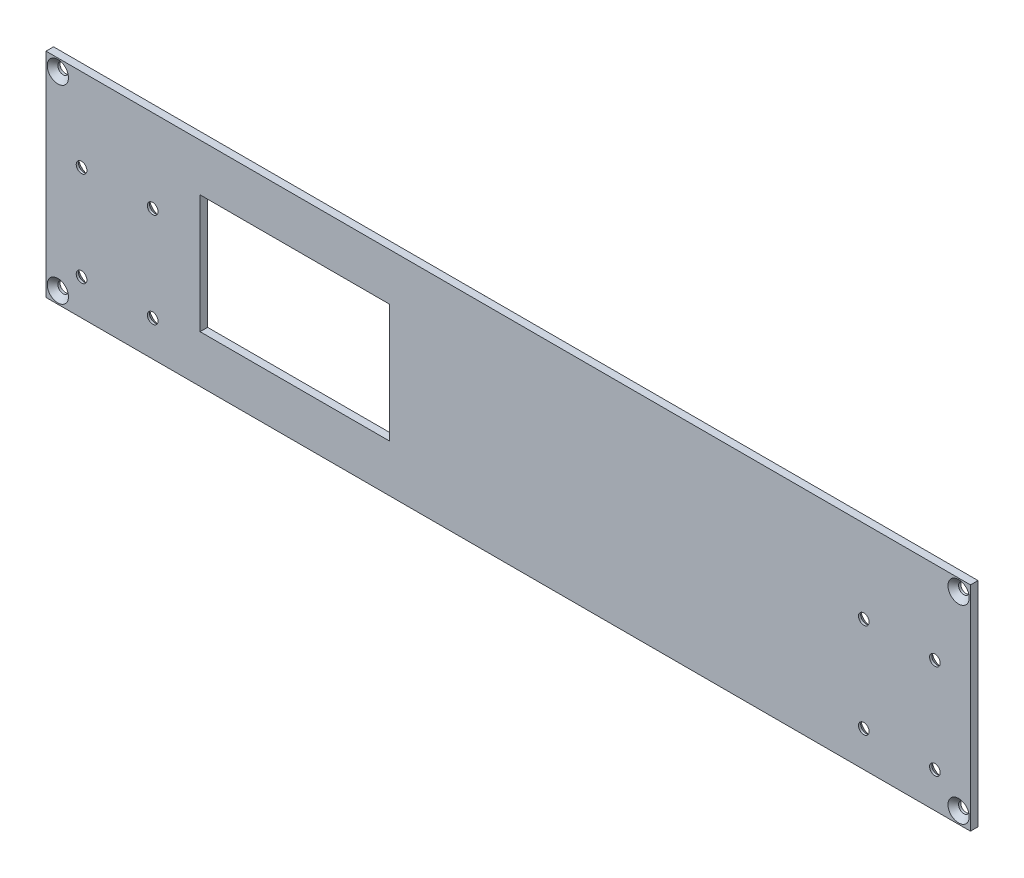
SolidWorks part; units mm, degrees
ref_plane "Front Plane" through (0, 0, 0) normal (0, 0, 1) x (1, 0, 0)
ref_plane "Top Plane" through (0, 0, 0) normal (0, 1, 0) x (1, 0, 0)
ref_plane "Right Plane" through (0, 0, 0) normal (1, 0, 0) x (0, 0, -1)
sketch "Sketch1" plane through (0, 0, 0) normal (0, 0, 1) x (1, 0, 0)
  line L1 (-195, -45) -> (195, -45)
  line L2 (-195, -45) -> (-195, 45)
  line L3 (-195, 45) -> (195, 45)
  line L4 (195, -45) -> (195, 45)
  line L5 (-195, -45) -> (195, 45) construction
  line L6 (-195, 45) -> (195, -45) construction
  point P0 (0, 0)
  dimension "D1" = 390
  dimension "D2" = 90
extrude "Boss-Extrude1" add sketch "Sketch1" along normal blind 3.175
hole_wizard "CSK for M4 SFHCS1" positions "Sketch3" profile "Sketch5" countersink size "M4" standard "ANSI Metric" end condition through all
sketch "Sketch3" plane through (0, 0, 0) normal (0, 0, -1) x (-1, 0, 0)
  line L1 (-180, -30) -> (-150, -30)
  line L2 (-180, -30) -> (-180, 10)
  line L3 (-180, 10) -> (-150, 10)
  line L4 (-150, -30) -> (-150, 10)
  line L5 (-180, -30) -> (-150, 10) construction
  line L6 (-180, 10) -> (-150, -30) construction
  line L7 (195, -45) -> (-195, -45) construction
  line L8 (-195, -45) -> (-195, 45) construction
  point P2 (-150, 10)
  point P69 (-180, -30)
  point P70 (-180, 10)
  point P71 (-150, -30)
  dimension "D1" = 30
  dimension "D2" = 40
  dimension "D3" = 15
  dimension "D4" = 15
sketch "Sketch5" plane through (150, 10, 0) normal (1, 0, 0) x (0, 1, 0)
  line L0 (0, 0) -> (0, 3.175)
  line L1 (0, 3.175) -> (2.25, 3.175)
  line L2 (2.25, 3.175) -> (2.25, 2.23)
  line L3 (2.25, 2.23) -> (4.48, 0)
  line L5 (4.48, 0) -> (0, 0)
  line L6 (-2.25, 2.23) -> (-4.48, 0) construction
  line L11 (0, -6.35) -> (0, 107.95) construction
  dimension "Thru Hole Dia." = 4.5
  dimension "Thru Hole Depth" = 3.175
  dimension "Near C'Sink Dia." = 8.96
  dimension "Near C'Sink Angle" = 90
hole_wizard "CSK for M4 SFHCS3" positions "Sketch6" profile "Sketch7" countersink size "M4" standard "ANSI Metric" end condition through all
sketch "Sketch6" plane through (0, 0, 3.175) normal (0, 0, 1) x (1, 0, 0)
  line L0 (190, 40) -> (190, -40)
  line L1 (195, -45) -> (195, 45) construction
  point P1 (190, 40)
  point P2 (190, -40)
  point P6 (190, 0)
  dimension "D1" = 80
  dimension "D2" = 5
sketch "Sketch7" plane through (190, 40, 3.175) normal (1, 0, 0) x (0, -1, 0)
  line L0 (0, 0) -> (0, 3.175)
  line L1 (0, 3.175) -> (2.25, 3.175)
  line L2 (2.25, 3.175) -> (2.25, 2.23)
  line L3 (2.25, 2.23) -> (4.48, 0)
  line L5 (4.48, 0) -> (0, 0)
  line L6 (-2.25, 2.23) -> (-4.48, 0) construction
  line L11 (0, -6.35) -> (0, 107.95) construction
  dimension "Thru Hole Dia." = 4.5
  dimension "Thru Hole Depth" = 3.175
  dimension "Near C'Sink Dia." = 8.96
  dimension "Near C'Sink Angle" = 90
mirror "Mirror1" about plane through (0, 0, 0) normal (1, 0, 0) of "CSK for M4 SFHCS1", "CSK for M4 SFHCS3"
sketch "Sketch8" plane through (0, 0, 3.175) normal (0, 0, 1) x (1, 0, 0)
  line L0 (-195, 45) -> (-195, -45) construction
  line L1 (-130, -25) -> (-50, -25)
  line L2 (-130, -25) -> (-130, 25)
  line L3 (-130, 25) -> (-50, 25)
  line L4 (-50, -25) -> (-50, 25)
  line L5 (-130, -25) -> (-50, 25) construction
  line L6 (-130, 25) -> (-50, -25) construction
  point P0 (-90, 0)
  point P5 (0, 0)
  dimension "D1" = 80
  dimension "D2" = 50
  dimension "D3" = 65
extrude "Cut-Extrude1" cut sketch "Sketch8" against normal blind 3.175
